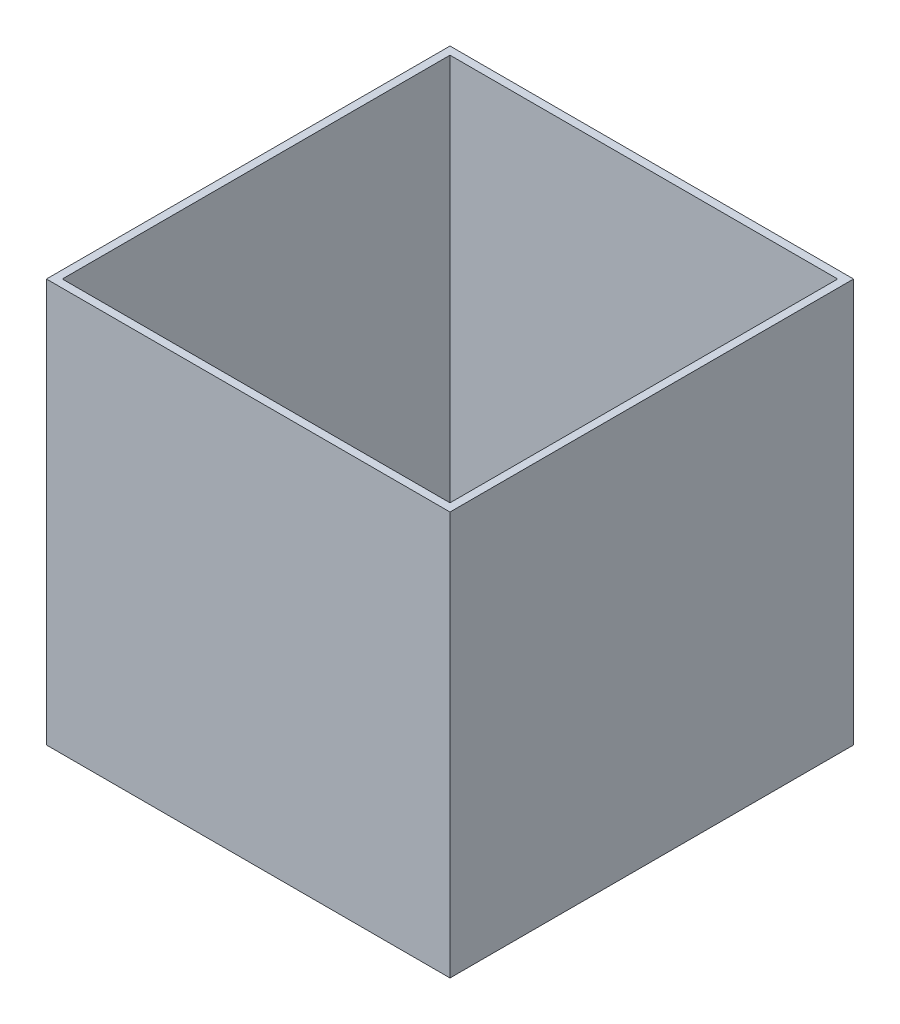
SolidWorks part; units mm, degrees
material "ABS"
ref_plane "Front Plane" through (0, 0, 0) normal (0, 0, 1) x (1, 0, 0)
ref_plane "Top Plane" through (0, 0, 0) normal (0, 1, 0) x (1, 0, 0)
ref_plane "Right Plane" through (0, 0, 0) normal (1, 0, 0) x (0, 0, -1)
sketch "Sketch1" plane through (0, 0, 0) normal (0, 1, 0) x (1, 0, 0)
  line L0 (-50.8, 50.8) -> (-50.8, -50.8)
  line L1 (-50.8, -50.8) -> (50.8, -50.8)
  line L2 (50.8, -50.8) -> (50.8, 50.8)
  line L3 (50.8, 50.8) -> (-50.8, 50.8)
  point P4 (0, 50.8)
  point P6 (-50.8, 0)
  dimension "D1" = 101.6
extrude "Boss-Extrude1" add sketch "Sketch1" along normal blind 101.6
sketch "Sketch2" plane through (0, 101.6, 0) normal (0, 1, 0) x (1, 0, 0)
  line L0 (48.8, 48.8) -> (-48.8, 48.8)
  line L1 (-48.8, 48.8) -> (-48.8, -48.8)
  line L2 (-48.8, -48.8) -> (48.8, -48.8)
  line L3 (48.8, -48.8) -> (48.8, 48.8)
  line L4 (50.8, 50.8) -> (-50.8, 50.8)
  line L5 (-50.8, 50.8) -> (-50.8, -50.8)
  line L6 (-50.8, -50.8) -> (50.8, -50.8)
  line L7 (50.8, -50.8) -> (50.8, 50.8)
  line L8 (50.8, 50.8) -> (-50.8, 50.8) construction
  line L9 (-50.8, 50.8) -> (-50.8, -50.8) construction
  line L10 (-50.8, -50.8) -> (50.8, -50.8) construction
  line L11 (50.8, -50.8) -> (50.8, 50.8) construction
  dimension "D1" = 0
  dimension "D2" = 2
extrude "Cut-Extrude1" cut sketch "Sketch2" against normal blind 99.6
